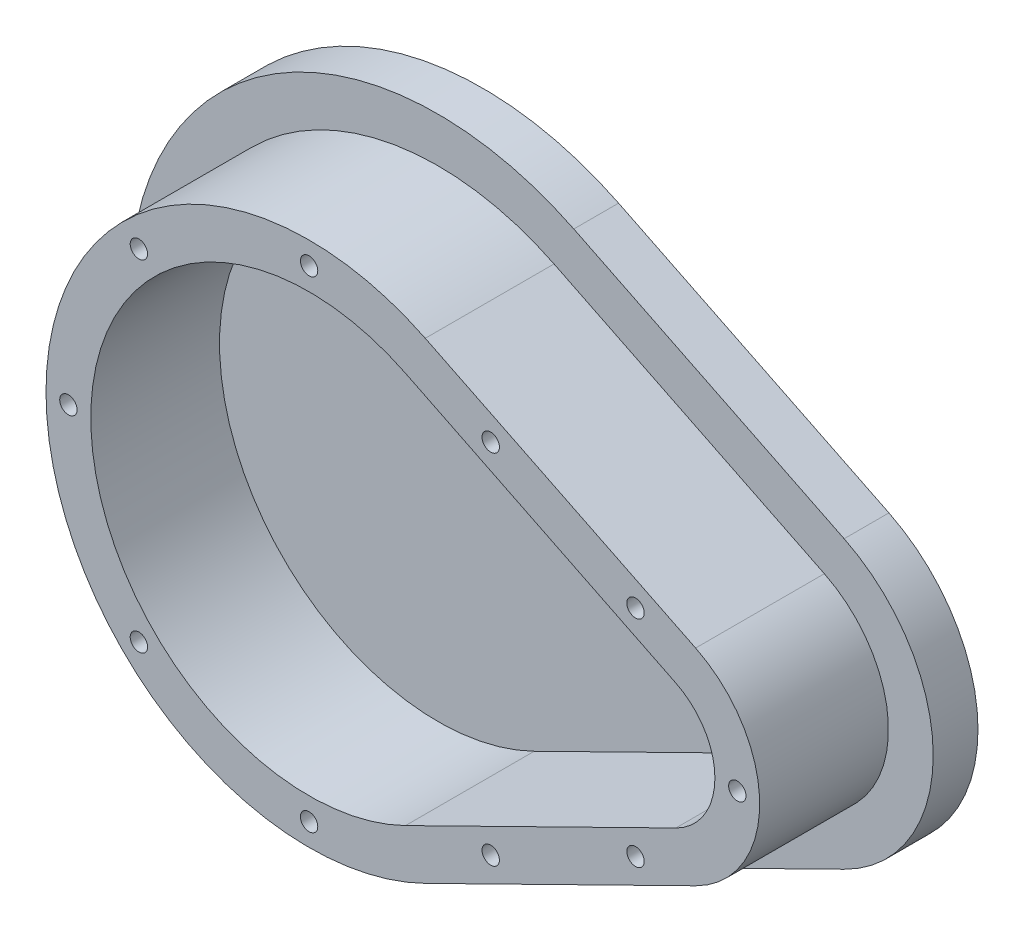
SolidWorks part; units mm, degrees
ref_plane "Front Plane" through (0, 0, 0) normal (0, 0, 1) x (1, 0, 0)
ref_plane "Top Plane" through (0, 0, 0) normal (0, 1, 0) x (1, 0, 0)
ref_plane "Right Plane" through (0, 0, 0) normal (1, 0, 0) x (0, 0, -1)
sketch "Sketch1" plane through (0, 0, 0) normal (0, 0, 1) x (1, 0, 0)
  line L0 (72.5875, 25.5696) -> (24.2917, 49.3449)
  line L1 (0, 0) -> (60, 0) construction
  line L5 (72.5875, -25.5696) -> (24.2917, -49.3449)
  circle A1 centre (0, 0) radius 55 construction
  circle A11 centre (60, 0) radius 28.5 construction
  arc A12 (24.2917, 49.3449) -> (24.2917, -49.3449) centre (0, 0) ccw
  arc A13 (72.5875, 25.5696) -> (72.5875, -25.5696) centre (60, 0) cw
  point P11 (0, 0)
  point P22 (0, 0)
extrude "Boss-Extrude2" add sketch "Sketch1" along normal blind 8
sketch "Sketch5" plane through (0, 0, 8) normal (0, 0, 1) x (1, 0, 0)
  line L0 (20.7583, 42.1674) -> (69.0542, 18.3922)
  line L1 (69.0542, -18.3922) -> (20.7583, -42.1674)
  line L2 (65.5208, 11.2147) -> (17.225, 34.99)
  line L3 (65.5208, -11.2147) -> (17.225, -34.99)
  circle A0 centre (0, 0) radius 43 construction
  circle A1 centre (60, 0) radius 16.5 construction
  circle A4 centre (60, 0) radius 12.5 construction
  circle A5 centre (60, 0) radius 20.5 construction
  circle A6 centre (0, 0) radius 39 construction
  circle A7 centre (0, 0) radius 47 construction
  arc A8 (20.7583, 42.1674) -> (20.7583, -42.1674) centre (0, 0) ccw
  arc A9 (69.0542, 18.3922) -> (69.0542, -18.3922) centre (60, 0) cw
  arc A10 (17.225, 34.99) -> (17.225, -34.99) centre (0, 0) ccw
  arc A11 (65.5208, 11.2147) -> (65.5208, -11.2147) centre (60, 0) cw
  point P21 (0, 0)
extrude "Boss-Extrude3" add sketch "Sketch5" along normal blind 23
sketch "Sketch6" plane through (0, 0, 31) normal (0, 0, 1) x (1, 0, 0)
  line L0 (0, 0) -> (0, 43) construction
  line L1 (60, 0) -> (76.5, 0) construction
  line L2 (20.7583, 42.1674) -> (69.0542, 18.3922) construction
  line L3 (20.7583, -42.1674) -> (69.0542, -18.3922) construction
  line L4 (20.7583, 42.1674) -> (34.216, 35.5424) construction
  line L5 (34.216, 35.5424) -> (32.4494, 31.9537) construction
  line L6 (69.0542, 18.3922) -> (60.0824, 22.8088) construction
  line L7 (60.0824, 22.8088) -> (58.3157, 19.2201) construction
  line L8 (20.7583, -42.1674) -> (34.216, -35.5424) construction
  line L9 (34.216, -35.5424) -> (32.4494, -31.9537) construction
  line L10 (69.0542, -18.3922) -> (60.0824, -22.8088) construction
  line L11 (60.0824, -22.8088) -> (58.3157, -19.2201) construction
  circle A1 centre (60, 0) radius 16.5 construction
  circle A2 centre (0, 0) radius 43 construction
  circle A3 centre (0, 43) radius 1.55
  circle A4 centre (-30.4056, 30.4056) radius 1.55
  circle A5 centre (-43, 0) radius 1.55
  circle A6 centre (-30.4056, -30.4056) radius 1.55
  circle A7 centre (0, -43) radius 1.55
  circle A8 centre (76.5, 0) radius 1.55
  circle A9 centre (0, 0) radius 47 construction
  circle A10 centre (60, 0) radius 20.5 construction
  arc A11 (69.0542, 18.3922) -> (69.0542, -18.3922) centre (60, 0) cw construction
  arc A12 (20.7583, 42.1674) -> (20.7583, -42.1674) centre (0, 0) ccw construction
  circle A13 centre (58.3157, 19.2201) radius 1.55
  circle A14 centre (32.4494, 31.9537) radius 1.55
  circle A15 centre (58.3157, -19.2201) radius 1.55
  circle A16 centre (32.4494, -31.9537) radius 1.55
  point P21 (0, 0)
  dimension "D1" = 5
extrude "Cut-Extrude1" cut sketch "Sketch6" against normal up to surface (31 mm away) up to face at (32.5948, 0, 0)
